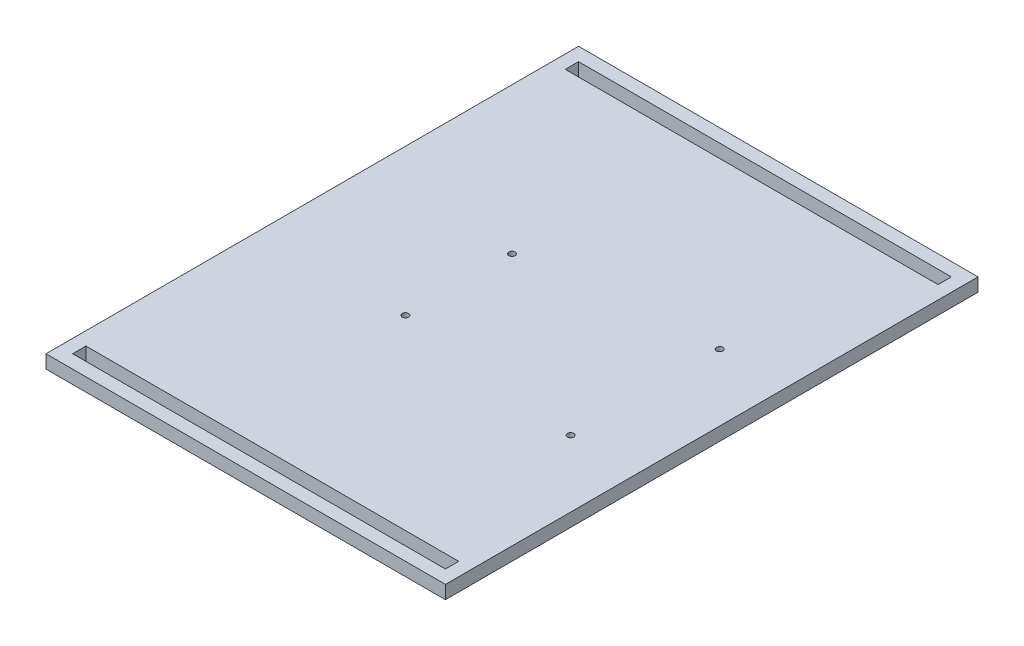
SolidWorks part; units mm, degrees
ref_plane "Front Plane" through (0, 0, 0) normal (0, 0, 1) x (1, 0, 0)
ref_plane "Top Plane" through (0, 0, 0) normal (0, 1, 0) x (1, 0, 0)
ref_plane "Right Plane" through (0, 0, 0) normal (1, 0, 0) x (0, 0, -1)
sketch "Sketch1" plane through (0, 0, 0) normal (0, 1, 0) x (1, 0, 0)
  line L1 (-75, 100) -> (75, 100)
  line L2 (-75, 100) -> (-75, -100)
  line L3 (-75, -100) -> (75, -100)
  line L4 (75, 100) -> (75, -100)
  line L5 (-75, 100) -> (75, -100) construction
  line L6 (-75, -100) -> (75, 100) construction
  point P0 (0, 0)
  dimension "D1" = 150
  dimension "D2" = 200
extrude "Boss-Extrude1" add sketch "Sketch1" along normal blind 100
shell "Shell2" thickness 5
sketch "Sketch5" plane through (0, 0, 0) normal (0, -1, 0) x (1, 0, 0)
  line L0 (-75, 100) -> (75, 100) construction
  circle A0 centre (-65, 91) radius 1.9
  circle A1 centre (-35, 91) radius 1.9
  circle A2 centre (-65, 67) radius 1.9
  circle A3 centre (-35, 67) radius 1.9
  dimension "D1" = 3.8
  dimension "D2" = 5
  dimension "D3" = 35
  dimension "D4" = 9
  dimension "D5" = 30
  dimension "D6" = 24
extrude "Cut-Extrude2" cut sketch "Sketch5" against normal blind 10
mirror "Mirror2" about plane through (0, 0, 0) normal (0, 0, 1) of "Cut-Extrude2"
sketch "Sketch6" plane through (0, 5, 0) normal (0, 1, 0) x (1, 0, 0)
  line L0 (-75, -100) -> (75, -100) construction
  line L1 (-70, 100) -> (-7.9429, 100) construction
  line L2 (-70, 100) -> (-70, -100) construction
  line L3 (-70, -100) -> (-7.9429, -100) construction
  line L4 (-7.9429, 100) -> (-7.9429, -100) construction
  line L10 (-70, -100) -> (-20, -100)
  line L11 (-70, -100) -> (-70, 100)
  line L12 (-70, 100) -> (-20, 100)
  line L13 (-20, -100) -> (-20, 100)
  dimension "D1" = 200
  dimension "D2" = 50
sketch "Sketch8" plane through (0, 0, 100) normal (0, 0, 1) x (1, 0, 0)
  line L3 (75, 17) -> (-15, 17)
  line L4 (-15, 0) -> (-15, 17)
  line L5 (75, 22) -> (-20, 22)
  line L6 (-20, 0) -> (-20, 22)
  line L8 (80, -5) -> (80, 22) construction
  line L9 (75, 0) -> (75, 17) construction
  line L10 (75, 0) -> (-15, 0) construction
  line L11 (80, -5) -> (-20, -5) construction
  line L12 (-15, 0) -> (-20, 0)
  line L13 (75, 17) -> (75, 22)
  line L14 (75, 100) -> (75, 0) construction
  line L15 (80, 22) -> (-20, 22) construction
  line L16 (-20, -5) -> (-20, 22) construction
  line L17 (-75, 0) -> (75, 0) construction
  line M3 (-75, 0) -> (75, 0)
  line M4 (75, 0) -> (75, 100)
  line M12 (70, 95) -> (70, 5)
  line M13 (70, 5) -> (-70, 5)
  dimension "D1" = 90
  dimension "D2" = 17
  dimension "D3" = 5
extrude "Boss-Extrude4" add sketch "Sketch8" against normal through all contours L6 L4 L3 L5 M13 M12 | L6 L4 M3 M13 | L5 L3 M4 M12
sketch "Sketch9" plane through (0, 0, 100) normal (0, 0, 1) x (1, 0, 0)
  line L1 (-15, 17) -> (86.1339, 17)
  line L2 (-15, 17) -> (-15, -14.9961)
  line L3 (-15, -14.9961) -> (86.1339, -14.9961)
  line L4 (86.1339, 17) -> (86.1339, -14.9961)
extrude "Cut-Extrude4" cut sketch "Sketch9" against normal through all
sketch "Sketch10" plane through (0, 17, 0) normal (0, -1, 0) x (1, 0, 0)
  line L0 (75, 100) -> (75, -100) construction
  circle A0 centre (60, 0) radius 4
  dimension "D1" = 8
  dimension "D2" = 15
extrude "Cut-Extrude5" cut sketch "Sketch10" against normal blind 10
sketch "Sketch11" plane through (0, 100, 0) normal (0, 1, 0) x (1, 0, 0)
  line L0 (-75, -100) -> (75, -100) construction
  line L1 (70, -95) -> (-70, -95)
  line L2 (70, -95) -> (70, -90)
  line L3 (70, -90) -> (-70, -90)
  line L4 (-70, -95) -> (-70, -90)
  line L5 (75, -100) -> (75, 100) construction
  line L6 (-75, 100) -> (-75, -100) construction
  point P6 (70, -92.5)
  dimension "D1" = 5
  dimension "D2" = 5
  dimension "D3" = 5
  dimension "D4" = 5
extrude "Cut-Extrude7" cut sketch "Sketch11" against normal up to surface (95 mm away) contours L4 L1 L2 L3 up to face at (-35, 5, -89.1)
mirror "Mirror3" about plane through (0, 0, 0) normal (0, 0, 1) of "Cut-Extrude7"
sketch "Sketch15" plane through (0, 100, 0) normal (0, 1, 0) x (1, 0, 0)
  circle A0 centre (50, 28) radius 1.2
  circle A1 centre (50, -28) radius 1.2
  circle A2 centre (-20, 20) radius 1.2
  circle A3 centre (-20, -20) radius 1.2
  dimension "D1" = 2.4
  dimension "D2" = 56
  dimension "D3" = 28
  dimension "D4" = 40
  dimension "D5" = 20
  dimension "D6" = 70
  dimension "D7" = 50
extrude "Cut-Extrude11" cut sketch "Sketch15" against normal blind 10
sketch "Sketch36" plane through (70, 0, 0) normal (-1, 0, 0) x (0, 0, 1)
  line L1 (-43.2021, 65) -> (16.7979, 65)
  line L2 (-43.2021, 65) -> (-43.2021, 60)
  line L3 (-43.2021, 60) -> (16.7979, 60)
  line L4 (16.7979, 65) -> (16.7979, 60)
  line L5 (-100, 0) -> (100, 0) construction
  point P6 (16.7979, 62.5)
  dimension "D1" = 65
  dimension "D2" = 5
  dimension "D3" = 16.7979
  dimension "D4" = 60
extrude "Boss-Extrude7" add sketch "Sketch36" along normal blind 10
mirror "Mirror5" about plane through (0, 0, 0) normal (1, 0, 0) of "Boss-Extrude7"
sketch "Sketch37" plane through (75, 0, 0) normal (1, 0, 0) x (0, 0, -1)
  circle A0 centre (0, 75) radius 3.5
  point P2 (0, 0)
  dimension "D1" = 7
  dimension "D2" = 75
extrude "Cut-Extrude15" cut sketch "Sketch37" against normal blind 60
sketch "Sketch38" plane through (-75, 0, 0) normal (-1, 0, 0) x (0, 0, 1)
  circle A0 centre (0, 80) radius 5
  point P2 (0, 0)
  dimension "D1" = 10
  dimension "D2" = 80
extrude "Cut-Extrude16" cut sketch "Sketch38" against normal blind 70
sketch "Sketch39" plane through (0, 0, 100) normal (0, 0, 1) x (1, 0, 0)
  line L0 (-75, 100) -> (-75, 0) construction
  line L1 (-75, 95) -> (81.493, 95)
  line L2 (-75, 95) -> (-75, -7.7027)
  line L3 (-75, -7.7027) -> (81.493, -7.7027)
  line L4 (81.493, 95) -> (81.493, -7.7027)
extrude "Cut-Extrude17" cut sketch "Sketch39" against normal through all
